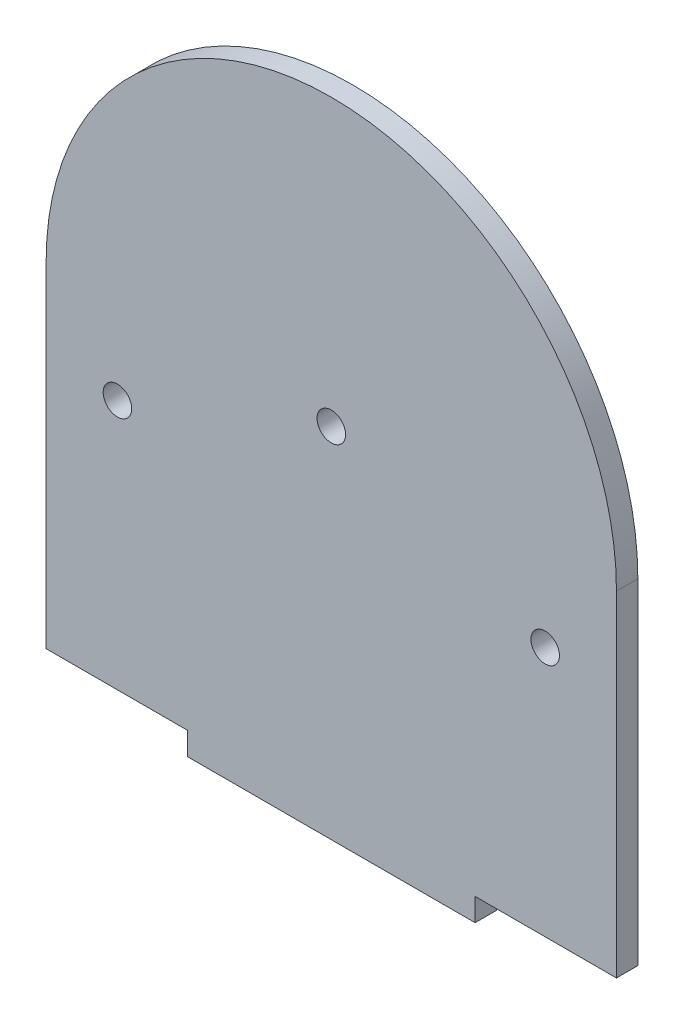
SolidWorks part; units mm, degrees
ref_plane "Front Plane" through (0, 0, 0) normal (0, 0, 1) x (1, 0, 0)
ref_plane "Top Plane" through (0, 0, 0) normal (0, 1, 0) x (1, 0, 0)
ref_plane "Right Plane" through (0, 0, 0) normal (1, 0, 0) x (0, 0, -1)
sketch "Croquis1" plane through (0, 0, 0) normal (0, 0, 1) x (1, 0, 0)
  line L3 (-20.175, -47) -> (20.175, -47) construction
  line L4 (40, 0) -> (40, -47)
  line L6 (0, 0) -> (28.2843, 28.2843) construction
  line L14 (0, 0) -> (40, 0) construction
  line L20 (0, 0) -> (0, -47) construction
  line L21 (-28.2843, 28.2843) -> (0, 0) construction
  line L23 (-20.175, -47) -> (-20.175, -50.2)
  line L25 (20.175, -50.2) -> (20.175, -47)
  line L26 (0, -50.2) -> (0, -47) construction
  line L27 (-40, 0) -> (-40, -47)
  line L28 (-40, -47) -> (-20.175, -47)
  line L29 (20.175, -47) -> (40, -47)
  line L32 (-20.175, -50.2) -> (20.175, -50.2) construction
  line L33 (-20.175, -50.2) -> (20.175, -50.2)
  arc A12 (-40, 0) -> (0, 40) centre (0, 0) cw
  arc A13 (40, 0) -> (0, 40) centre (0, 0) ccw
  circle A15 centre (-30, -11.85) radius 2
  circle A16 centre (30, -11.85) radius 2
  circle A17 centre (0, 0) radius 2
  point P0 (0, 0)
  point P13 (0, 2)
  point P37 (0, -51.5)
  dimension "D3" = 4.5
  dimension "D4" = 80
  dimension "D5" = 45
  dimension "D6" = 45
  dimension "D14" = 35.15
  dimension "D10" = 4
  dimension "D11" = 4
  dimension "D2" = 87
  dimension "D7" = 3.2
  dimension "D8" = 40.35
  dimension "D9" = 47
  dimension "D13" = 10
extrude "Saliente-Extruir1" add sketch "Croquis1" along normal blind 3
